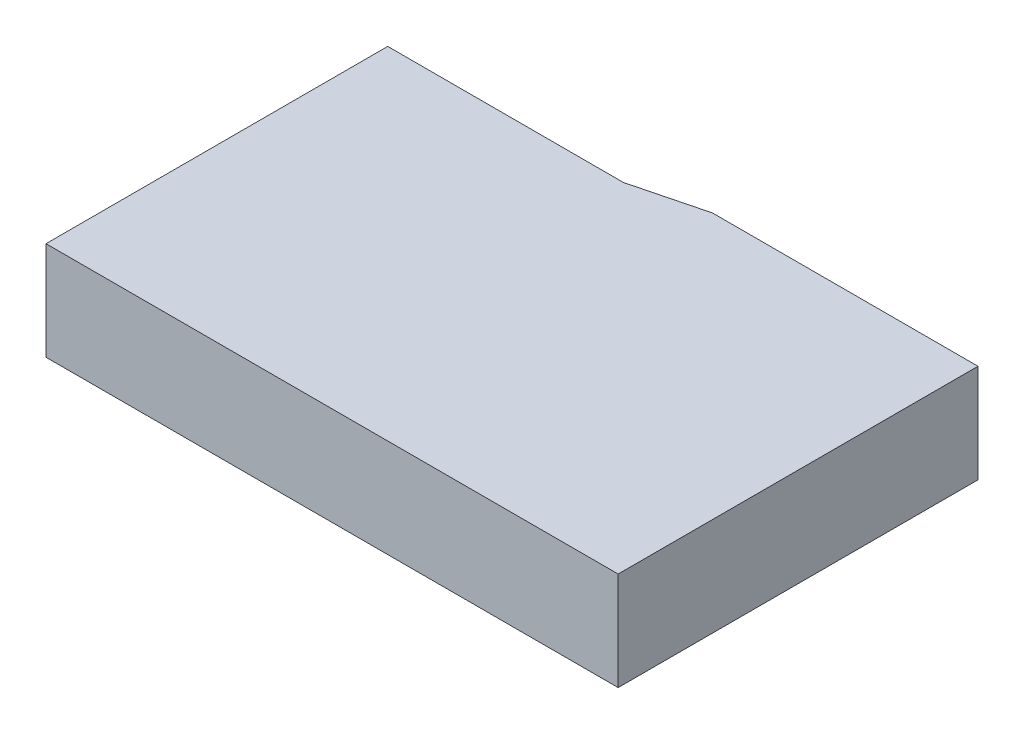
SolidWorks part; units mm, degrees
ref_plane "前视基准面" through (0, 0, 0) normal (0, 0, 1) x (1, 0, 0)
ref_plane "上视基准面" through (0, 0, 0) normal (0, 1, 0) x (1, 0, 0)
ref_plane "右视基准面" through (0, 0, 0) normal (1, 0, 0) x (0, 0, -1)
other "Configuration Table"
sketch "草图1" plane through (0, 0, 0) normal (0, 1, 0) x (1, 0, 0)
  line L1 (0, 0) -> (110.5, 0)
  line L2 (0, 0) -> (0, -66)
  line L3 (0, -66) -> (110.5, -66)
  line L4 (110.5, 0) -> (110.5, -66)
  dimension "D1" = 110.5
  dimension "D2" = 66
extrude "凸台-拉伸1" add sketch "草图1" along normal blind 19
sketch "草图2" plane through (0, 19, 0) normal (0, 1, 0) x (1, 0, 0)
  line L0 (110.5, 0) -> (45.5311, 0)
  line L1 (110.5, 0) -> (0, 0) construction
  line L2 (45.5311, 0) -> (59.218, 3.5)
  line L3 (59.218, 3.5) -> (110.5, 3.5)
  line L4 (110.5, 3.5) -> (110.5, 0)
  dimension "D1" = 3.5
extrude "凸台-拉伸2" add sketch "草图2" against normal up to surface (19 mm away) up to face at (55.25, 0, 33)
